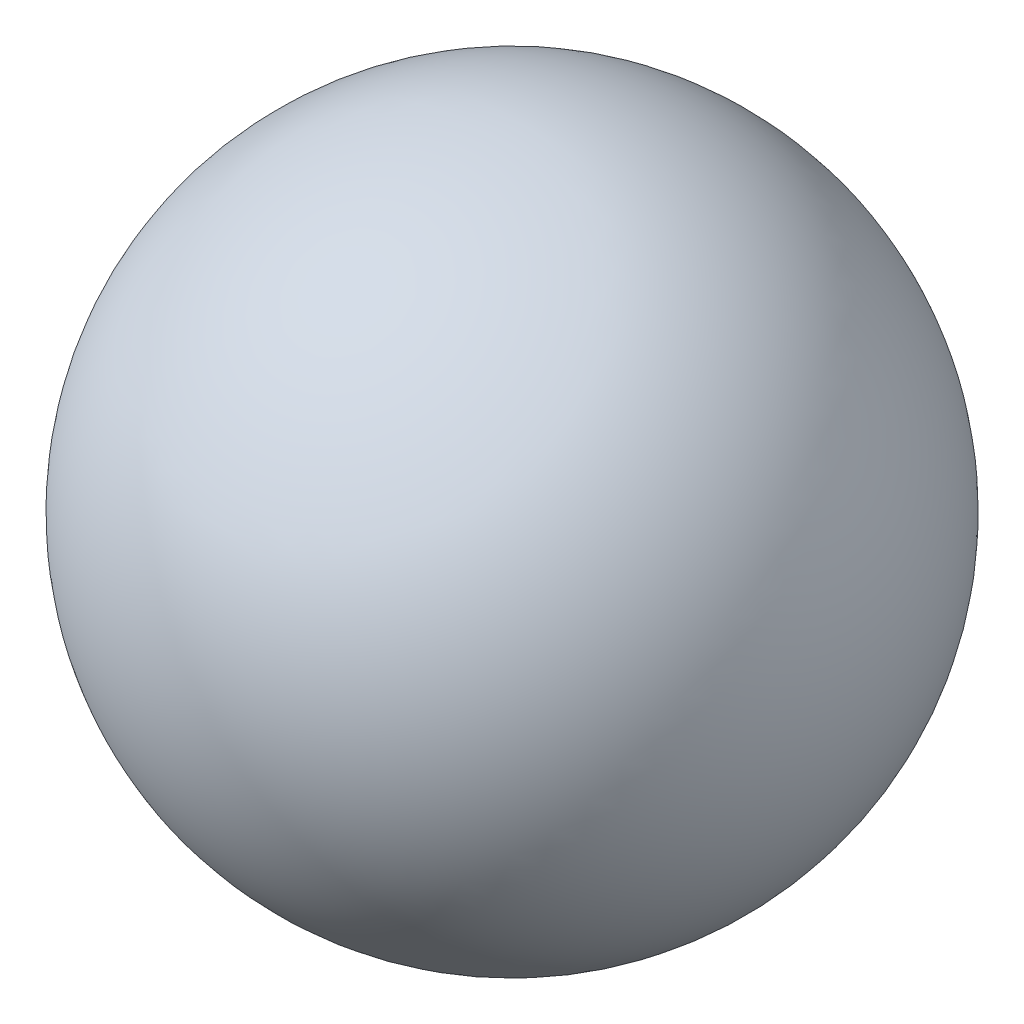
SolidWorks part; units mm, degrees
ref_plane "Front Plane" through (0, 0, 0) normal (0, 0, 1) x (1, 0, 0)
ref_plane "Top Plane" through (0, 0, 0) normal (0, 1, 0) x (1, 0, 0)
ref_plane "Right Plane" through (0, 0, 0) normal (1, 0, 0) x (0, 0, -1)
sketch "Sketch2" plane through (0, 0, 0) normal (0, 1, 0) x (1, 0, 0)
  line L0 (0, 0) -> (0, 80)
  arc A0 (0, 80) -> (0, 0) centre (0, 40) cw
  point P4 (11.6141, 40)
  point P5 (0, 0)
  point P6 (0, 40)
  dimension "D1" = 80
  dimension "D2" = 0
revolve "Revolve1" add sketch "Sketch2" angle 360 about L0
